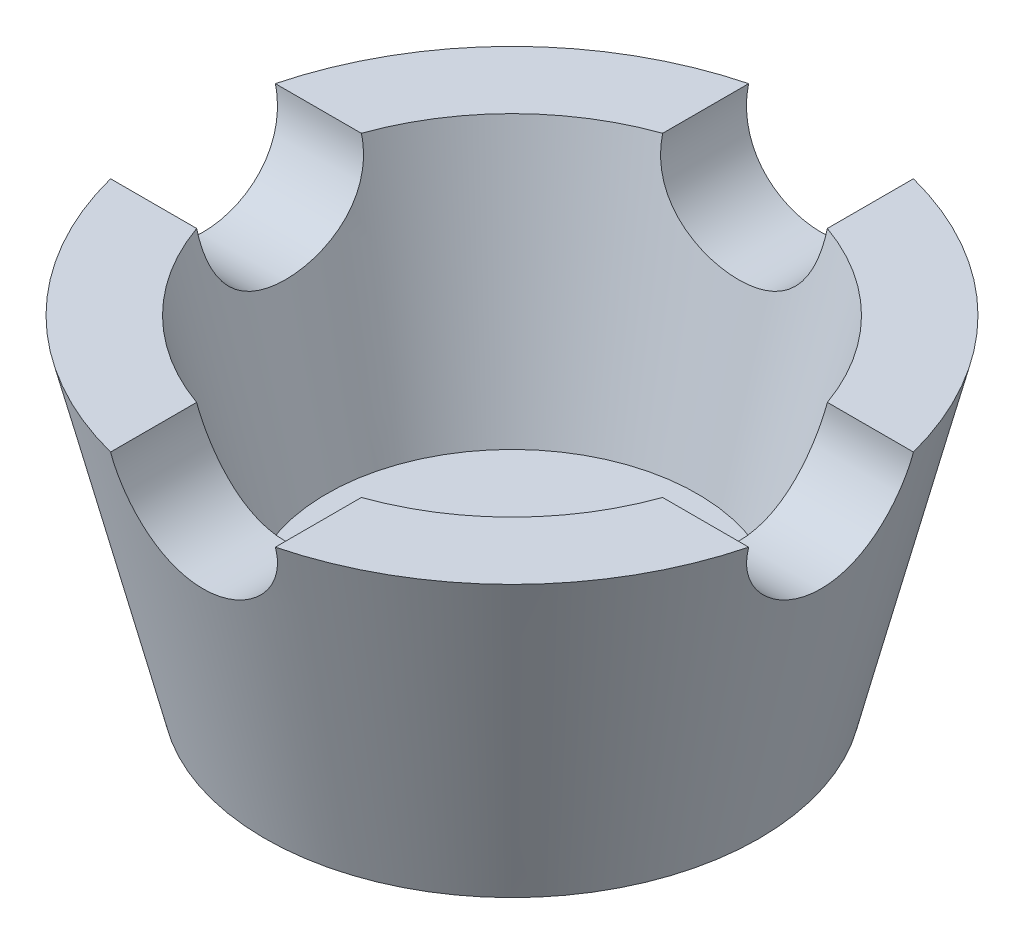
SolidWorks part; units mm, degrees
ref_plane "Front Plane" through (0, 0, 0) normal (0, 0, 1) x (1, 0, 0)
ref_plane "Top Plane" through (0, 0, 0) normal (0, 1, 0) x (1, 0, 0)
ref_plane "Right Plane" through (0, 0, 0) normal (1, 0, 0) x (0, 0, -1)
sketch "Sketch1" plane through (0, 0, 0) normal (0, 0, 1) x (1, 0, 0)
  line L0 (0, 0) -> (75, 0)
  line L1 (75, 0) -> (100, 100)
  line L2 (100, 100) -> (75, 100)
  line L3 (75, 100) -> (56.25, 25)
  line L4 (56.25, 25) -> (0, 25)
  line L5 (0, 25) -> (0, 0)
  line L6 (0, 0) -> (0, 131.6962) construction
  point P3 (100, 100)
  dimension "D1" = 75
  dimension "D2" = 100
  dimension "D3" = 100
  dimension "D4" = 25
  dimension "D5" = 25
revolve "Revolve1" add sketch "Sketch1" angle 360 about L6
sketch "Sketch2" plane through (0, 25, 0) normal (0, 1, 0) x (1, 0, 0)
  circle A0 centre (0, 0) radius 25
  dimension "D1" = 50
extrude "Cut-Extrude2" cut sketch "Sketch2" against normal blind 30
sketch "Sketch3" plane through (0, 0, 0) normal (1, 0, 0) x (0, 0, -1)
  line L0 (100, 100) -> (-100, 100) construction
  circle A0 centre (0, 100) radius 25
  point P0 (0, 100)
  dimension "D1" = 50
extrude "Cut-Extrude3" cut sketch "Sketch3" against normal through all both and the other way through all
sketch "Sketch4" plane through (0, 0, 0) normal (0, 0, 1) x (1, 0, 0)
  line L0 (96.8246, 100) -> (-96.8246, 100) construction
  circle A0 centre (0, 100) radius 25
  point P0 (0, 100)
  dimension "D1" = 50
extrude "Cut-Extrude4" cut sketch "Sketch4" against normal mid plane 200
